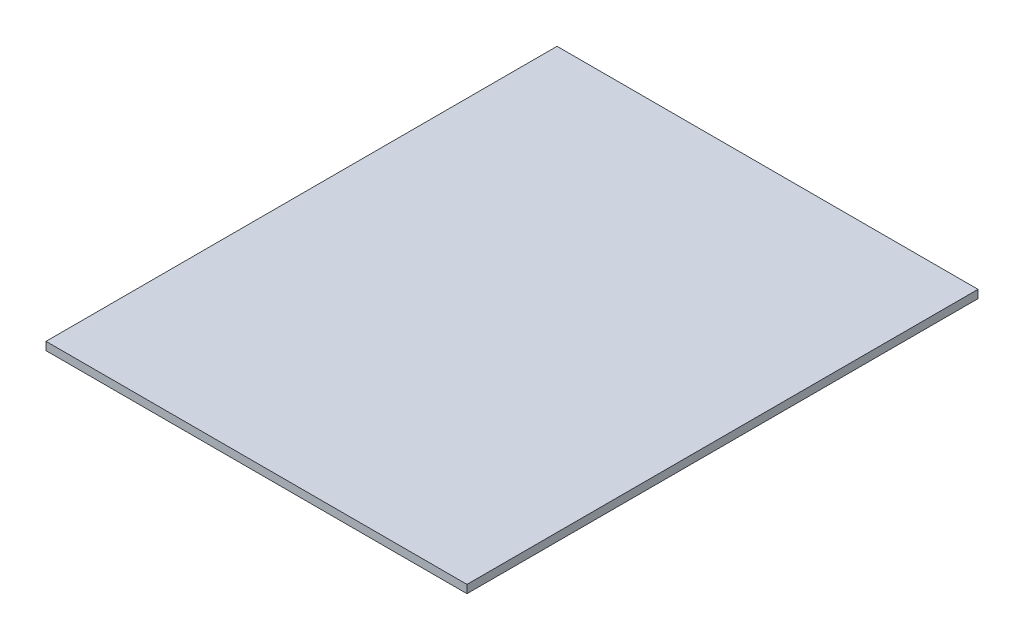
SolidWorks part; units mm, degrees
ref_plane "Front Plane" through (0, 0, 0) normal (0, 0, 1) x (1, 0, 0)
ref_plane "Top Plane" through (0, 0, 0) normal (0, 1, 0) x (1, 0, 0)
ref_plane "Right Plane" through (0, 0, 0) normal (1, 0, 0) x (0, 0, -1)
other "Configuration Table"
sketch "Sketch1" plane through (0, 0, 0) normal (0, 0, 1) x (1, 0, 0)
  line L1 (714, 1497) -> (1338, 1497)
  line L2 (714, 1497) -> (714, 1509)
  line L3 (714, 1509) -> (1338, 1509)
  line L4 (1338, 1497) -> (1338, 1509)
extrude "DET2_raf_alt_1" add sketch "Sketch1" against normal blind 757.5 separate body
